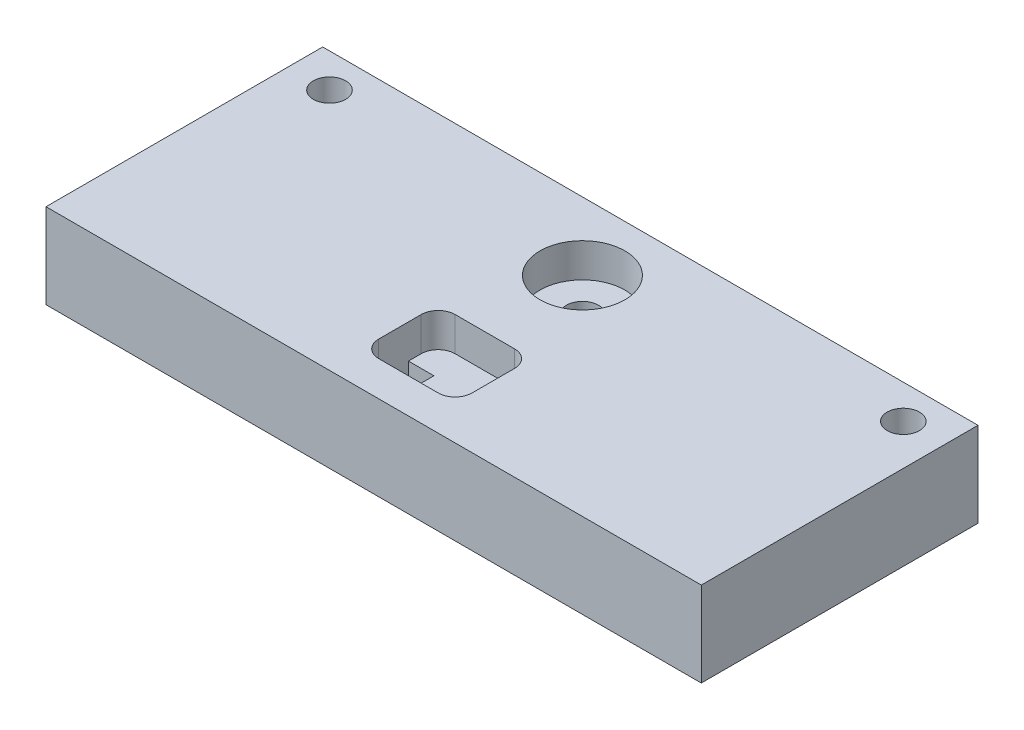
SolidWorks part; units mm, degrees
ref_plane "前视基准面" through (0, 0, 0) normal (0, 0, 1) x (1, 0, 0)
ref_plane "上视基准面" through (0, 0, 0) normal (0, 1, 0) x (1, 0, 0)
ref_plane "右视基准面" through (0, 0, 0) normal (1, 0, 0) x (0, 0, -1)
other "Configuration Table"
sketch "草图1" plane through (0, 0, 0) normal (0, 1, 0) x (1, 0, 0)
  line L0 (0, 0) -> (0, -50000) construction
  line L1 (-1.75, 2.25) -> (1.75, 2.25)
  line L2 (-2.75, 1.25) -> (-2.75, -1.25)
  line L3 (-1.75, -2.25) -> (1.75, -2.25)
  line L4 (2.75, 1.25) -> (2.75, -1.25)
  line L5 (-2.75, 2.25) -> (2.75, -2.25) construction
  line L6 (-2.75, -2.25) -> (2.75, 2.25) construction
  line L7 (0, 0) -> (50000, 0) construction
  line L9 (-5, 12) -> (5, 12)
  line L10 (-5, 12) -> (-5, -4.3)
  line L11 (-5, -4.3) -> (5, -4.3)
  line L12 (5, 12) -> (5, -4.3)
  arc A0 (-1.75, 2.25) -> (-2.75, 1.25) centre (-1.75, 1.25) ccw
  arc A1 (1.75, 2.25) -> (2.75, 1.25) centre (1.75, 1.25) cw
  arc A2 (2.75, -1.25) -> (1.75, -2.25) centre (1.75, -1.25) cw
  arc A3 (-2.75, -1.25) -> (-1.75, -2.25) centre (-1.75, -1.25) ccw
  circle A4 centre (0, 8) radius 2.5
  point P0 (0, 0)
  point P26 (0, 12)
  dimension "D3" = 1
  dimension "D4" = 1
  dimension "D5" = 5
  dimension "D1" = 4.5
  dimension "D2" = 5.5
  dimension "D6" = 4
  dimension "D7" = 12
  dimension "D8" = 16.3
  dimension "D9" = 10
extrude "凸台-拉伸1" add sketch "草图1" along normal blind 2
sketch "草图3" plane through (0, 0, 0) normal (0, -1, 0) x (1, 0, 0)
  line L0 (5, 4.3) -> (5, -12) construction
  line L1 (-5, 4.3) -> (5, 4.3)
  line L2 (-5, 4.3) -> (-5, -12)
  line L3 (-5, -12) -> (5, -12)
  line L4 (5, 4.3) -> (5, -12)
  line L14 (5, -12) -> (-5, -12) construction
  line L15 (0.1714, 0) -> (-49999.8286, 0) construction
  line L16 (-2.75, -1.25) -> (-2.75, 1.25) construction
  line L17 (-1.25, -0.5) -> (-2.75, -0.5)
  line L18 (-1.25, -0.5) -> (-1.25, 0.5)
  line L19 (-1.25, 0.5) -> (-2.75, 0.5)
  line L20 (-2.75, -0.5) -> (-2.75, 0.5)
  line L21 (-1.25, -0.5) -> (-2.75, 0.5) construction
  line L22 (-1.25, 0.5) -> (-2.75, -0.5) construction
  line L23 (2.75, 1.25) -> (2.75, -1.25) construction
  line L24 (1.25, -0.5) -> (2.75, -0.5)
  line L25 (1.25, -0.5) -> (1.25, 0.5)
  line L26 (1.25, 0.5) -> (2.75, 0.5)
  line L27 (2.75, -0.5) -> (2.75, 0.5)
  line L28 (1.25, -0.5) -> (2.75, 0.5) construction
  line L29 (1.25, 0.5) -> (2.75, -0.5) construction
  circle A5 centre (0, -8) radius 0.95
  point P11 (-2, 0)
  point P21 (2, 0)
  dimension "D1" = 1.5
  dimension "D2" = 1.5
  dimension "D3" = 1
  dimension "D4" = 4
  dimension "D5" = 1
extrude "凸台-拉伸2" add sketch "草图3" along normal blind 3
sketch "草图4" plane through (0, -3, 0) normal (0, -1, 0) x (1, 0, 0)
  line L1 (5, -12) -> (19.3, -12)
  line L2 (5, -12) -> (5, 4.3)
  line L3 (5, 4.3) -> (19.3, 4.3)
  line L4 (19.3, -12) -> (19.3, 4.3)
  line L5 (-5, -12) -> (-19.3, -12)
  line L6 (-5, -12) -> (-5, 4.3)
  line L7 (-5, 4.3) -> (-19.3, 4.3)
  line L8 (-19.3, -12) -> (-19.3, 4.3)
  line L10 (5, -12) -> (5, 4.3) construction
  line L11 (-5, 4.3) -> (-5, -12) construction
  line L12 (-5, -12) -> (5, -12) construction
  line L13 (5, 4.3) -> (-5, 4.3) construction
  dimension "D1" = 14.3
  dimension "D2" = 14.3
extrude "凸台-拉伸3" add sketch "草图4" against normal blind 5
sketch "草图5" plane through (0, 2, 0) normal (0, 1, 0) x (1, 0, 0)
  line L0 (-16.9, 10.4575) -> (-16.9, -49989.5425) construction
  line L1 (16.9, 10.3408) -> (16.9, -49989.6592) construction
  line L2 (17.7224, 10) -> (-49982.2776, 10) construction
  line L3 (-19.3, -4.3) -> (-19.3, 12) construction
  line L4 (19.3, 12) -> (19.3, -4.3) construction
  line L6 (19.3, 12) -> (-19.3, 12) construction
  circle A0 centre (-16.9, 10) radius 0.95
  circle A1 centre (16.9, 10) radius 0.95
  dimension "D4" = 1.9
  dimension "D5" = 1.9
  dimension "D1" = 2.4
  dimension "D2" = 2.4
  dimension "D3" = 2
extrude "切除-拉伸1" cut sketch "草图5" against normal blind 5
sketch "草图6" plane through (0, -3, 0) normal (0, -1, 0) x (1, 0, 0)
  line L0 (-8.5, -0.153) -> (-8.5, -50000.153) construction
  line L1 (8.5, 0.0792) -> (8.5, -49999.9208) construction
  line L2 (-19.3, 4.3) -> (-19.3, -12) construction
  line L3 (19.3, -12) -> (19.3, 4.3) construction
  line L4 (19.3, 4.3) -> (-19.3, 4.3) construction
  line L5 (-11, 2.3) -> (-6, 2.3)
  line L6 (-11, 2.3) -> (-11, -7.7)
  line L7 (-11, -7.7) -> (-6, -7.7)
  line L8 (-6, 2.3) -> (-6, -7.7)
  line L9 (-11, 2.3) -> (-6, -7.7) construction
  line L10 (-11, -7.7) -> (-6, 2.3) construction
  line L11 (6, 2.3) -> (11, 2.3)
  line L12 (6, 2.3) -> (6, -7.7)
  line L13 (6, -7.7) -> (11, -7.7)
  line L14 (11, 2.3) -> (11, -7.7)
  line L15 (6, 2.3) -> (11, -7.7) construction
  line L16 (6, -7.7) -> (11, 2.3) construction
  point P8 (-8.5, -2.7)
  point P13 (8.5, -2.7)
  dimension "D1" = 10.8
  dimension "D2" = 10.8
  dimension "D3" = 2
  dimension "D4" = 2
  dimension "D5" = 10
  dimension "D6" = 5
  dimension "D7" = 5
  dimension "D8" = 10
extrude "切除-拉伸2" cut sketch "草图6" against normal blind 3
equation "\"4、10.8\"=7.10579"
